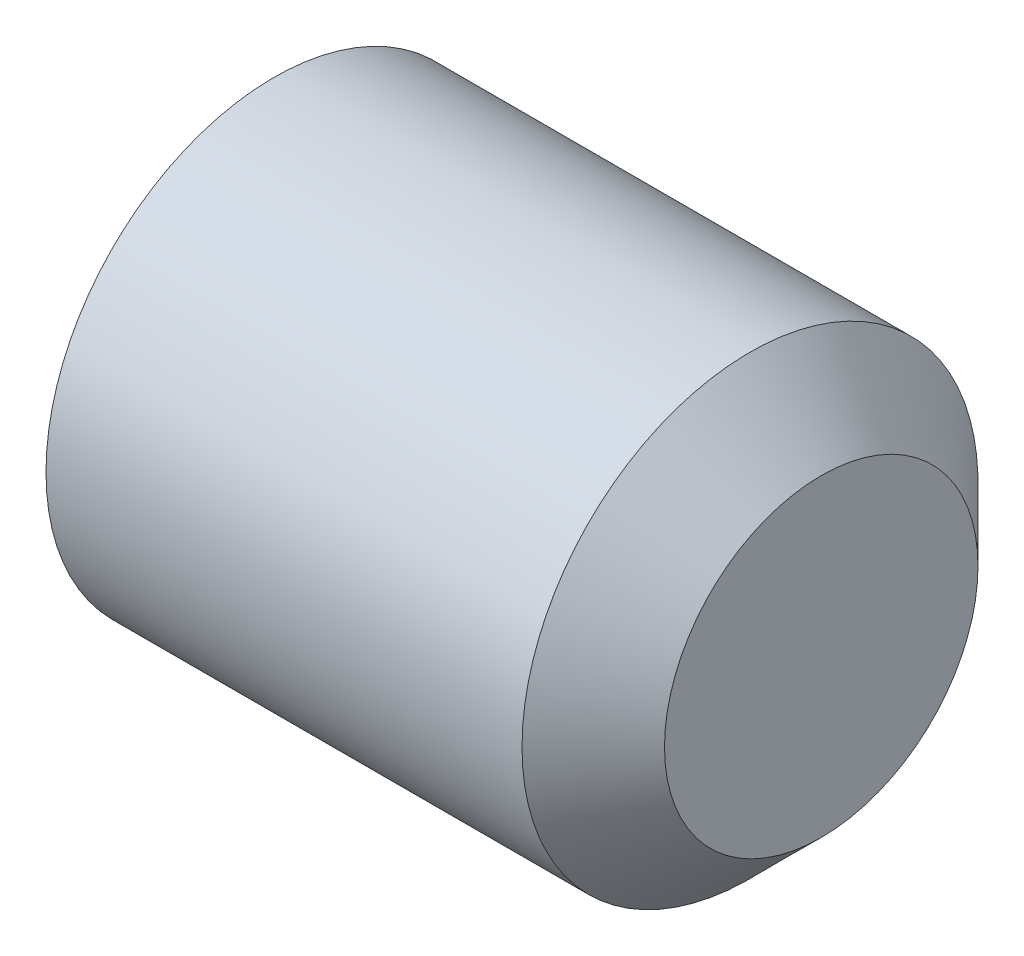
SolidWorks part; units mm, degrees
ref_plane "Plane1" through (0, 0, 0) normal (0, 0, 1) x (1, 0, 0)
ref_plane "Plane2" through (0, 0, 0) normal (0, 1, 0) x (1, 0, 0)
ref_plane "Plane3" through (0, 0, 0) normal (1, 0, 0) x (0, 0, -1)
sketch "BodySke" plane through (0, 0, 0) normal (0, 0, 1) x (1, 0, 0)
  line L0 (0, 0) -> (0, 3.3095)
  line L1 (0, 3.3095) -> (0.3987, 4)
  line L2 (0.3987, 4) -> (8.75, 4)
  line L3 (8.75, 4) -> (10, 2.75)
  line L4 (10, 0) -> (0, 0)
  line L5 (-12.7, 0) -> (88.9, 0) construction
  line L6 (10, 2.75) -> (10, 0)
  line L7 (10, 2.75) -> (10, 12.275) construction
  line L8 (0, -3.3095) -> (0.3987, -4) construction
  line L9 (1.25, 15.875) -> (1.25, -3.175) construction
  line L10 (8.75, -4) -> (10, -2.75) construction
  dimension "Length" = 10
  dimension "Diameter" = 8
  dimension "Drive_ch_ang" = 60
  dimension "Minor_dia" = 6.619
  dimension "Cup_nose_ang" = 45
  dimension "Cup_dia" = 5.5
  dimension "Advance" = 1.25
revolve "BaseBody" add sketch "BodySke" angle 360 about L5
cosmetic thread "ThreadCosmetic" [suppressed] parameters "Thread_minor"=6.619
sketch "Sketch2" plane through (0, 0, 0) normal (-1, 0, 0) x (0, 0, 1)
  line L0 (1.1547, 2) -> (-1.1547, 2)
  line L1 (-1.1547, 2) -> (-2.3094, 0)
  line L2 (1.1547, 2) -> (2.3094, 0)
  line L3 (1.1547, -2) -> (2.3094, 0)
  line L4 (1.1547, -2) -> (-1.1547, -2)
  line L5 (-1.1547, -2) -> (-2.3094, 0)
  dimension "Hex_size" = 4
  dimension "D2" = 2
  dimension "D3" = 2
extrude "Hex" cut sketch "Sketch2" against normal blind 5
sketch "ThdSchSke" plane through (0, 0, 0) normal (0, 0, 1) x (1, 0, 0)
  line L0 (0.3987, -3.3095) -> (-0.0848, -4)
  line L1 (0.3987, -3.3095) -> (0.8822, -4)
  line L2 (0.8822, -4) -> (0.8822, -5)
  line L3 (-3.175, 0) -> (5.1513, 0) construction
  line L5 (0.8822, -5) -> (-0.0848, -5)
  line L6 (-0.0848, -5) -> (-0.0848, -4)
  line L8 (0.3987, 4) -> (0.3987, -4) construction
  dimension "Thread_minor" = 6.619
  dimension "Diameter" = 8
  dimension "SideAngle" = 55
  dimension "VeeAngle" = 70
  dimension "Overcut" = 10
revolve "ThreadSchematic" [suppressed] cut sketch "ThdSchSke" angle 360 about L3
pattern_linear "ThdSchPat" [suppressed]
equation "\"D2@Sketch2\" = \"Hex_size@Sketch2\" / 2"
equation "\"D3@Sketch2\" = \"Hex_size@Sketch2\" / 2"
equation "\"Thread_minor@ThreadCosmetic\" = \"Minor_dia@BodySke\""
equation "\"Thread_minor@ThdSchSke\" = \"Thread_minor@ThreadCosmetic\""
equation "\"Diameter@ThdSchSke\" = \"Diameter@BodySke\""
equation "\"Overcut@ThdSchSke\" = \"Diameter@BodySke\" * 1.25"
equation "\"Num_threads@ThdSchPat\" = int( (\"Length@BodySke\" - ( ( ( \"Diameter@BodySke\" - \"Minor_dia@BodySke\" ) * 0.5 ) / tan( \"Drive_ch_ang@BodySke\" * 0.017453292 ) ) - ( ( ( \"Diameter@BodySke\" - \"Cup_dia@BodySke\" ) * 0.5 ) * tan( \"Cup_nose_ang@BodySke\" * 0.017453292 ) ) ) / \"Advance@BodySke\" + 0.999 )  + 1"
equation "\"Advance@ThdSchPat\" = (\"Length@BodySke\" - ( ( ( \"Diameter@BodySke\" - \"Minor_dia@BodySke\" ) * 0.5 ) / tan( \"Drive_ch_ang@BodySke\" * 0.017453292 ) ) - ( ( ( \"Diameter@BodySke\" - \"Cup_dia@BodySke\" ) * 0.5 ) * tan( \"Cup_nose_ang@BodySke\" * 0.017453292 ) ) ) /  (\"Num_threads@ThdSchPat\" - 1) 'relax it"
equation "' \"Num_threads@ThdSchPat\" = \"Num_threads@ThdSchPat\" - sgn( \"Num_threads@ThdSchPat\" - 1) '---chamfered tips only---"
